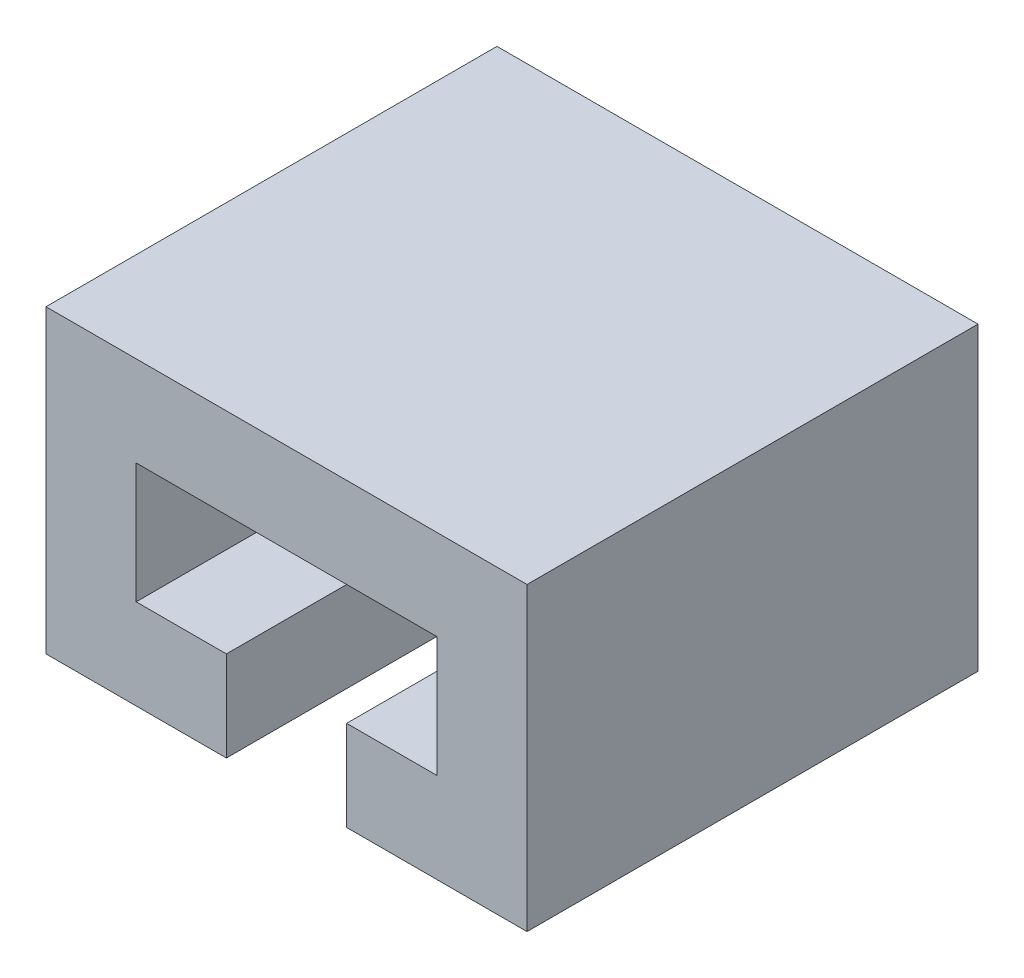
SolidWorks part; units mm, degrees
ref_plane "前视基准面" through (0, 0, 0) normal (0, 0, 1) x (1, 0, 0)
ref_plane "上视基准面" through (0, 0, 0) normal (0, 1, 0) x (1, 0, 0)
ref_plane "右视基准面" through (0, 0, 0) normal (1, 0, 0) x (0, 0, -1)
other "Configuration Table"
sketch "草图1" plane through (0, 0, 0) normal (0, 0, 1) x (1, 0, 0)
  line L0 (0, 0) -> (16, 0)
  line L1 (16, 0) -> (16, -10)
  line L2 (16, -10) -> (10, -10)
  line L3 (10, -10) -> (10, -7)
  line L4 (10, -7) -> (13, -7)
  line L5 (13, -7) -> (13, -3)
  line L6 (13, -3) -> (3, -3)
  line L7 (3, -3) -> (3, -7)
  line L8 (3, -7) -> (6, -7)
  line L9 (6, -7) -> (6, -10)
  line L10 (6, -10) -> (0, -10)
  line L11 (0, -10) -> (0, 0)
  point P3 (13, -5)
  dimension "D1" = 16
  dimension "D2" = 3
  dimension "D3" = 6
  dimension "D4" = 6
  dimension "D5" = 3
  dimension "D6" = 3
  dimension "D7" = 10
  dimension "D8" = 10
  dimension "D9" = 4
  dimension "D10" = 10
extrude "凸台-拉伸1" add sketch "草图1" along normal blind 15
